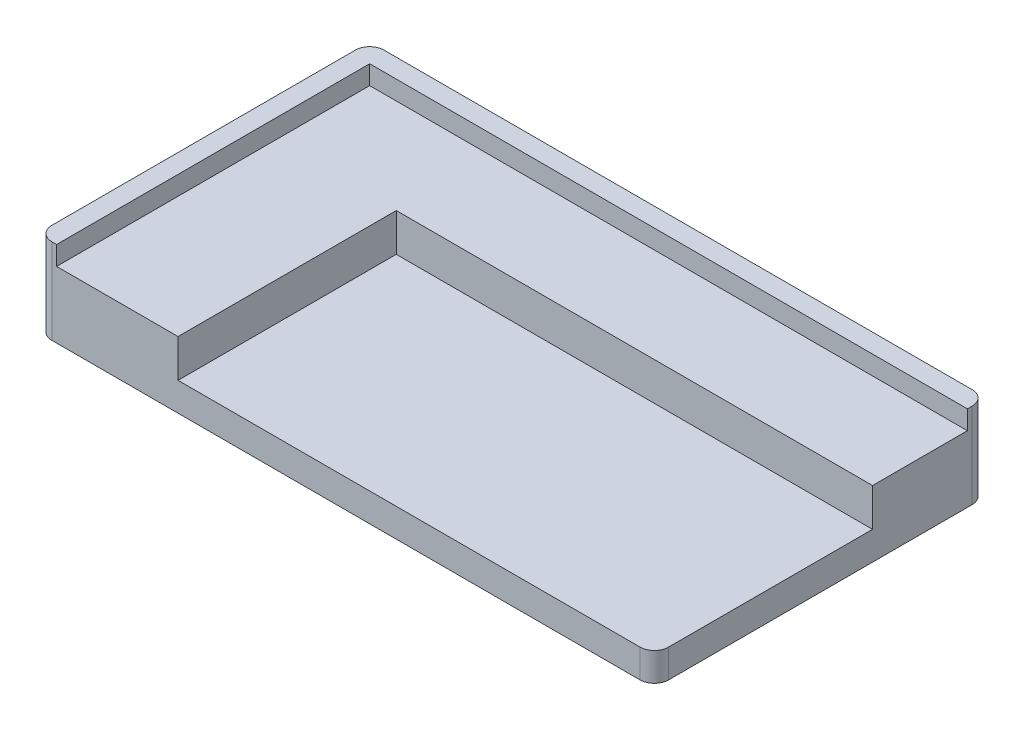
SolidWorks part; units mm, degrees
ref_plane "Front Plane" through (0, 0, 0) normal (0, 0, 1) x (1, 0, 0)
ref_plane "Top Plane" through (0, 0, 0) normal (0, 1, 0) x (1, 0, 0)
ref_plane "Right Plane" through (0, 0, 0) normal (1, 0, 0) x (0, 0, -1)
sketch "Sketch1" plane through (0, 0, 0) normal (0, 1, 0) x (1, 0, 0)
  line L1 (0, 0) -> (65, 0)
  line L2 (0, 0) -> (0, 35)
  line L3 (0, 35) -> (65, 35)
  line L4 (65, 0) -> (65, 35)
  dimension "D1" = 65
  dimension "D2" = 35
extrude "Boss-Extrude1" add sketch "Sketch1" along normal blind 9
sketch "Sketch2" plane through (0, 9, 0) normal (0, 1, 0) x (1, 0, 0)
  line L1 (2, 33) -> (65, 33)
  line L2 (2, 33) -> (2, 0)
  line L3 (2, 0) -> (65, 0)
  line L4 (65, 33) -> (65, 0)
  line L5 (0, 0) -> (65, 0) construction
  line L6 (65, 35) -> (0, 35) construction
  line L8 (65, 0) -> (65, 35) construction
  line L9 (0, 35) -> (0, 0) construction
  point P12 (0, 0)
  dimension "D1" = 2
  dimension "D2" = 2
extrude "Cut-Extrude1" cut sketch "Sketch2" against normal blind 2
sketch "Sketch3" plane through (0, 7, 0) normal (0, 1, 0) x (1, 0, 0)
  line L0 (65, 33) -> (2, 33) construction
  line L1 (14.8, 0) -> (65, 0)
  line L2 (14.8, 0) -> (14.8, 23)
  line L3 (14.8, 23) -> (65, 23)
  line L6 (65, 23) -> (65, 0)
  line L8 (65, 0) -> (65, 33) construction
  line L9 (2, 33) -> (2, 0) construction
  dimension "D1" = 10
  dimension "D2" = 12.8
extrude "Cut-Extrude2" cut sketch "Sketch3" against normal blind 4
fillet "Fillet1" radius 1.5 4 edges at (0, 4.5, 0) (65, 1.5, 0) (0, 4.5, -35) (65, 4.5, -35)
